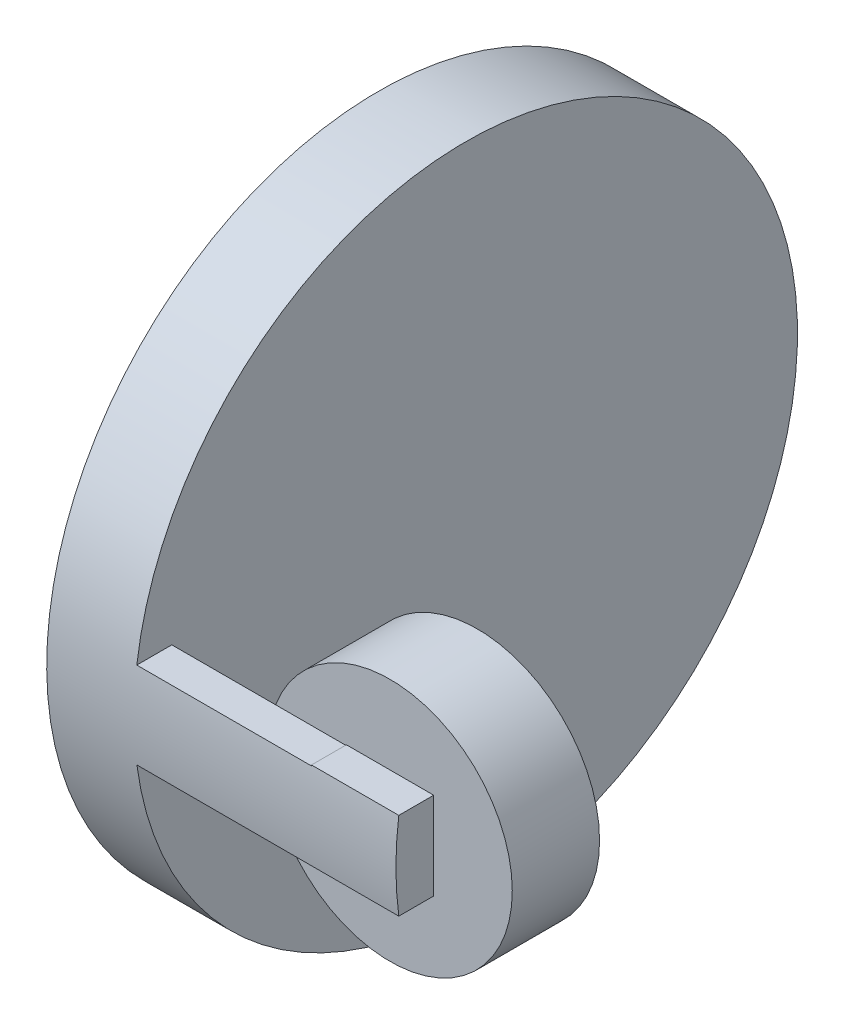
SolidWorks part; units mm, degrees
ref_plane "Front Plane" through (0, 0, 0) normal (0, 0, 1) x (1, 0, 0)
ref_plane "Top Plane" through (0, 0, 0) normal (0, 1, 0) x (1, 0, 0)
ref_plane "Right Plane" through (0, 0, 0) normal (1, 0, 0) x (0, 0, -1)
sketch "Sketch1" plane through (0, 0, 0) normal (0, 0, 1) x (1, 0, 0)
  circle A0 centre (0, 0) radius 14
  circle A1 centre (0, 0) radius 10
  circle A2 centre (0, 0) radius 5.5
extrude "Boss-Extrude1" add sketch "Sketch1" along normal blind 10 contours A0
sketch "Sketch2" plane through (0, 0, 0) normal (0, 0, -1) x (-1, 0, 0)
  circle A0 centre (0, 0) radius 2.25
extrude "Cut-Extrude1" cut sketch "Sketch2" against normal blind 5
sketch "Sketch3" plane through (0, 0, 0) normal (0, 0, -1) x (-1, 0, 0)
  circle A0 centre (0, 0) radius 5
extrude "Cut-Extrude2" cut sketch "Sketch3" against normal blind 1.8
sketch "Sketch4" plane through (0, 0, 10) normal (0, 0, 1) x (1, 0, 0)
  line L1 (-5, 5) -> (5, 5)
  line L2 (-5, 5) -> (-5, -5)
  line L3 (-5, -5) -> (5, -5)
  line L4 (5, 5) -> (5, -5)
  line L5 (-5, 5) -> (5, -5) construction
  line L6 (-5, -5) -> (5, 5) construction
  point P0 (0, 0)
  dimension "D1" = 10
  dimension "D2" = 10
extrude "Boss-Extrude2" add sketch "Sketch4" along normal blind 8
sketch "Sketch6" plane through (-5, 0, 0) normal (-1, 0, 0) x (0, 0, 1)
  line L0 (10, 5) -> (10, -5) construction
  line L1 (10, 4.9129) -> (18, 4.9129)
  line L2 (10, 4.9129) -> (10, -5)
  line L3 (10, -5) -> (18, -5)
  line L4 (18, 4.9129) -> (18, -5)
extrude "Boss-Extrude3" add sketch "Sketch6" along normal blind 20
sketch "Sketch7" plane through (5, 0, 0) normal (1, 0, 0) x (0, 0, -1)
  line L0 (-18, 5) -> (-18, -5)
  line L1 (-18, -5) -> (-14, -5)
  line L2 (-18, -5) -> (-10, -5) construction
  line L3 (-18, 5) -> (-14, 5)
  line L4 (-18, 5) -> (-10, 5) construction
  arc A2 (-14, -5) -> (-14, 5) centre (23.6696, 0) cw
extrude "Cut-Extrude3" cut sketch "Sketch7" against normal blind 30
sketch "Sketch8" plane through (-25, 0, 0) normal (-1, 0, 0) x (0, 0, 1)
  circle A0 centre (-23.6696, 0) radius 38
extrude "Boss-Extrude4" add sketch "Sketch8" along normal blind 10
sketch "Sketch9" plane through (-35, 0, 0) normal (-1, 0, 0) x (0, 0, 1)
  circle A0 centre (-23.6696, 0.9929) radius 29
extrude "Boss-Extrude5" add sketch "Sketch9" along normal blind 5
